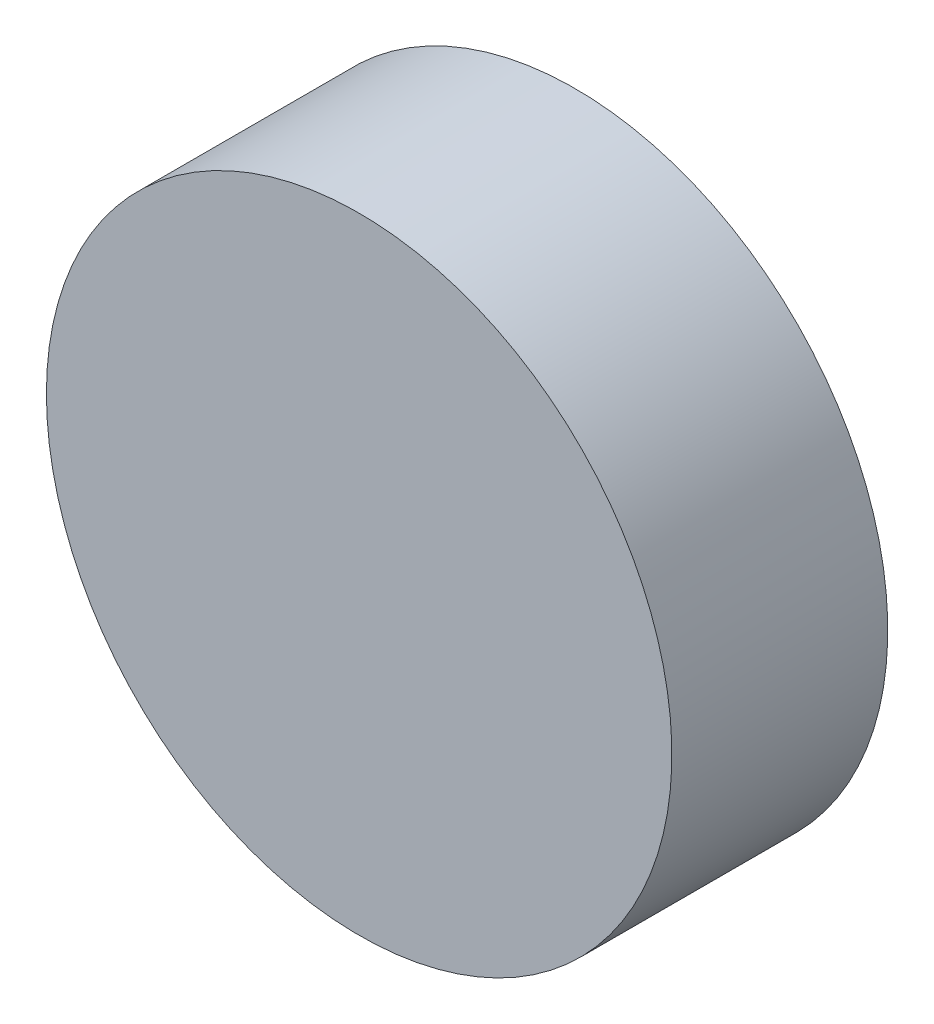
SolidWorks part; units mm, degrees
ref_plane "Front Plane" through (0, 0, 0) normal (0, 0, 1) x (1, 0, 0)
ref_plane "Top Plane" through (0, 0, 0) normal (0, 1, 0) x (1, 0, 0)
ref_plane "Right Plane" through (0, 0, 0) normal (1, 0, 0) x (0, 0, -1)
sketch "CurveSketch" plane through (0, 0, 0) normal (0, 0, 1) x (1, 0, 0)
  circle A0 centre (3.917, -5.139) radius 11.173
  dimension "D1" = 22.346
extrude "CurveBoss" add sketch "CurveSketch" along normal blind 7.713
